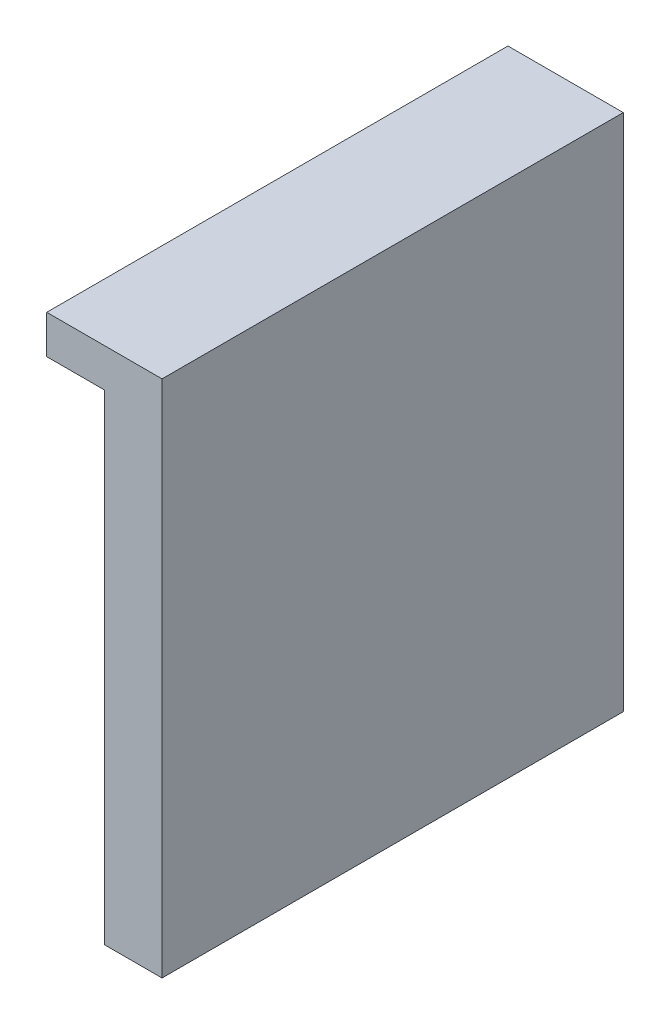
SolidWorks part; units mm, degrees
ref_plane "Front Plane" through (0, 0, 0) normal (0, 0, 1) x (1, 0, 0)
ref_plane "Top Plane" through (0, 0, 0) normal (0, 1, 0) x (1, 0, 0)
ref_plane "Right Plane" through (0, 0, 0) normal (1, 0, 0) x (0, 0, -1)
sketch "Sketch1" plane through (0, 0, 0) normal (0, 1, 0) x (1, 0, 0)
  line L1 (0, 0) -> (3, 0)
  line L2 (0, 0) -> (0, 24)
  line L3 (0, 24) -> (3, 24)
  line L4 (3, 0) -> (3, 24)
  dimension "D1" = 3
  dimension "D2" = 24
extrude "Boss-Extrude1" add sketch "Sketch1" along normal blind 23 contours L2 L1 L4 L3
sketch "Sketch2" plane through (0, 23, 0) normal (0, 1, 0) x (1, 0, 0)
  line L0 (0, 24) -> (3, 24) construction
  line L1 (3, 0) -> (-3, 0)
  line L2 (3, 0) -> (3, 24)
  line L3 (3, 24) -> (-3, 24)
  line L4 (-3, 0) -> (-3, 24)
  dimension "D1" = 6
extrude "Boss-Extrude2" add sketch "Sketch2" along normal blind 2 contours L2 L1 L4 L3
sketch "Sketch3" plane through (0, 0, 0) normal (-1, 0, 0) x (0, 0, 1)
  line L0 (0, 23) -> (-24, 23) construction
  line L1 (-23, 12) -> (-1, 12)
  line L2 (-23, 12) -> (-23, 21)
  line L3 (-23, 21) -> (-1, 21)
  line L4 (-1, 12) -> (-1, 21)
  line L5 (0, 23) -> (0, 0) construction
  line L6 (-24, 23) -> (-24, 0) construction
  dimension "D1" = 2
  dimension "D2" = 1
  dimension "D3" = 1
  dimension "D4" = 9
extrude "Cut-Extrude1" cut sketch "Sketch3" against normal blind 1
sketch "Sketch4" plane through (0, 0, 0) normal (0, -1, 0) x (1, 0, 0)
  line L1 (0, 0) -> (3, 0)
  line L2 (0, 0) -> (0, -24)
  line L3 (0, -24) -> (3, -24)
  line L4 (3, 0) -> (3, -24)
extrude "Boss-Extrude3" add sketch "Sketch4" along normal blind 2
